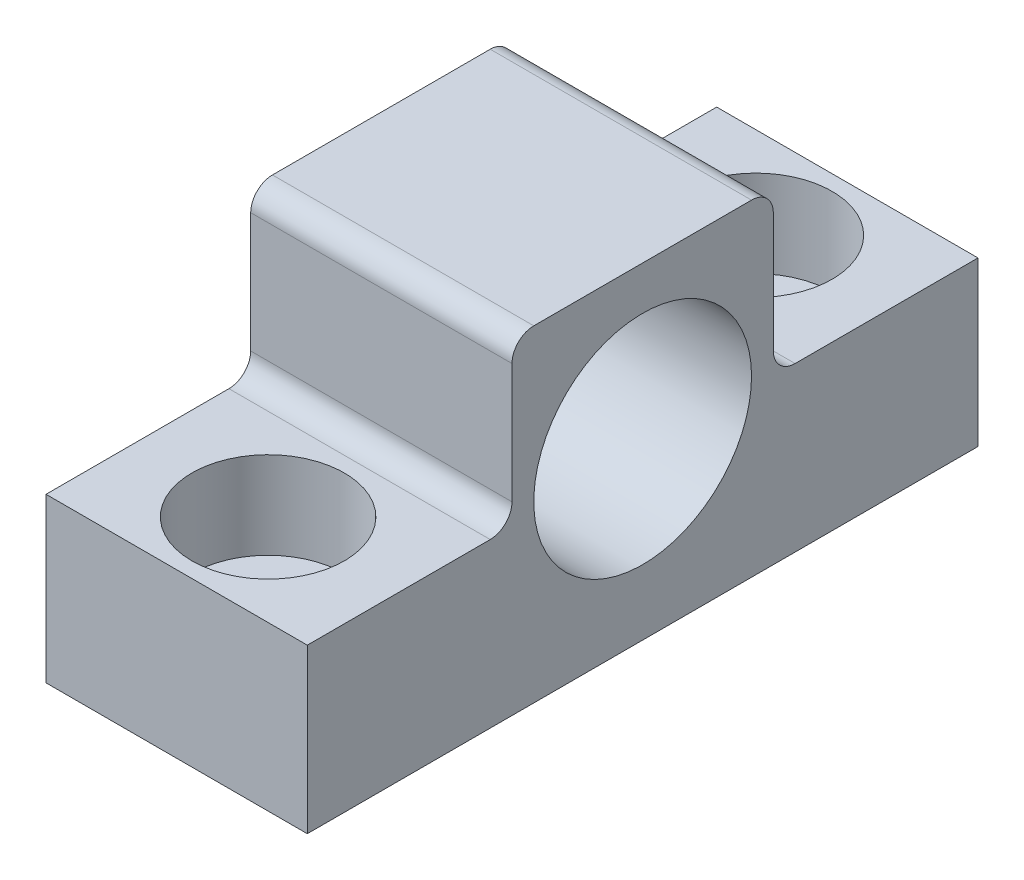
SolidWorks part; units mm, degrees
ref_plane "Front Plane" through (0, 0, 0) normal (0, 0, 1) x (1, 0, 0)
ref_plane "Top Plane" through (0, 0, 0) normal (0, 1, 0) x (1, 0, 0)
ref_plane "Right Plane" through (0, 0, 0) normal (1, 0, 0) x (0, 0, -1)
sketch "Sketch2" plane through (0, 0, 0) normal (1, 0, 0) x (0, 0, -1)
  line L0 (0, 0) -> (12, 0)
  line L1 (12, 0) -> (12, -7.5)
  line L2 (12, -7.5) -> (21.4, -7.5)
  line L3 (21.4, -7.5) -> (21.4, -15)
  line L4 (21.4, -15) -> (-9.4, -15)
  line L5 (-9.4, -15) -> (-9.4, -7.5)
  line L6 (0, 0) -> (0, -7.5)
  line L7 (0, -7.5) -> (-9.4, -7.5)
  dimension "D1" = 9.4
  dimension "D2" = 9.4
  dimension "D3" = 12
  dimension "D4" = 15
  dimension "D5" = 7.5
  dimension "D6" = 7.5
extrude "Boss-Extrude1" add sketch "Sketch2" along normal blind 10
sketch "Sketch3" plane through (10, 0, 0) normal (1, 0, 0) x (0, 0, -1)
  line L0 (12, 0) -> (0, 0) construction
  circle A0 centre (6, -7) radius 5
  dimension "D1" = 7
extrude "Cut-Extrude1" cut sketch "Sketch3" against normal up to next contours A0
sketch "Sketch4" plane through (0, 0, 0) normal (-1, 0, 0) x (0, 0, 1)
  line L8 (0, -7.5) -> (0, 0)
  line L9 (0, 0) -> (-12, 0)
  line L10 (-12, 0) -> (-12, -7.5)
  line L11 (-12, -7.5) -> (-21.4, -7.5)
  line L12 (-21.4, -7.5) -> (-21.4, -15)
  line L13 (-21.4, -15) -> (9.4, -15)
  line L14 (9.4, -15) -> (9.4, -7.5)
  line L15 (9.4, -7.5) -> (0, -7.5)
  line L16 (0, -7.5) -> (0, 0)
  line L17 (0, 0) -> (-12, 0)
  line L18 (-12, 0) -> (-12, -7.5)
  line L19 (-12, -7.5) -> (-21.4, -7.5)
  line L20 (-21.4, -7.5) -> (-21.4, -15)
  line L21 (-21.4, -15) -> (9.4, -15)
  line L22 (9.4, -15) -> (9.4, -7.5)
  line L23 (9.4, -7.5) -> (0, -7.5)
  dimension "D1" = 0
extrude "Boss-Extrude2" add sketch "Sketch4" along normal blind 2
fillet "Fillet1" radius 1 4 edges at (4, 0, 0) (4, 0, -12) (4, -7.5, -12) (4, -7.5, 0)
sketch "Sketch5" plane through (0, -7.5, 0) normal (0, 1, 0) x (1, 0, 0)
  circle A0 centre (4, 17.2) radius 2
  circle A1 centre (4, -5.2) radius 2
extrude "Cut-Extrude2" cut sketch "Sketch5" against normal up to next
sketch "Sketch6" plane through (0, -7.5, 0) normal (0, 1, 0) x (1, 0, 0)
  circle A0 centre (4, -5.2) radius 3.5
  circle A1 centre (4, 17.2) radius 3.5
extrude "Cut-Extrude3" cut sketch "Sketch6" against normal blind 4
